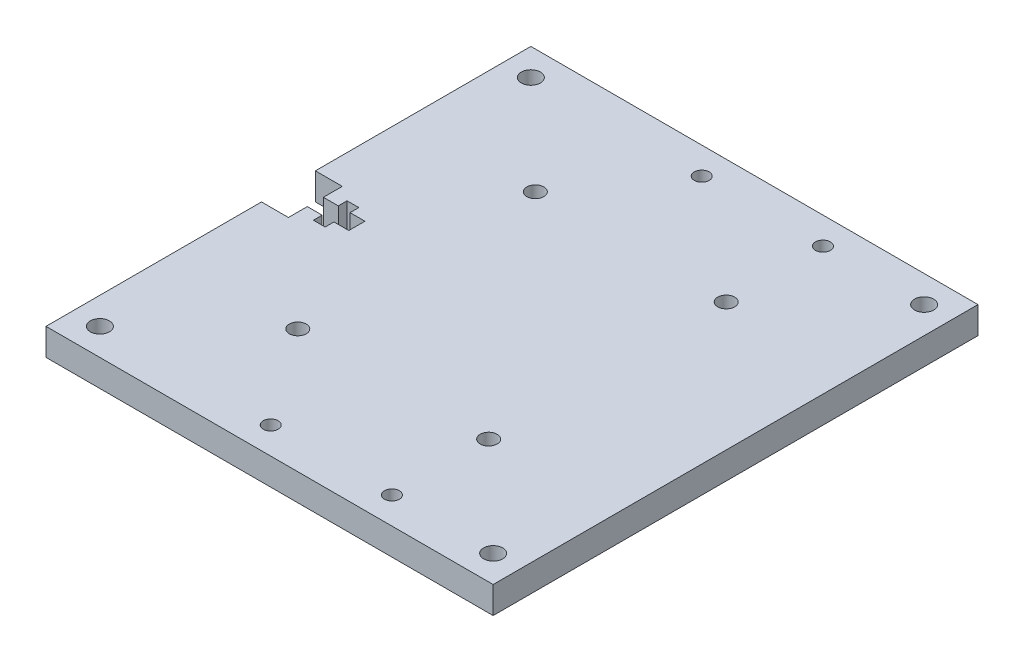
SolidWorks part; units mm, degrees
material "Beech"
ref_plane "Front Plane" through (0, 0, 0) normal (0, 0, 1) x (1, 0, 0)
ref_plane "Top Plane" through (0, 0, 0) normal (0, 1, 0) x (1, 0, 0)
ref_plane "Right Plane" through (0, 0, 0) normal (1, 0, 0) x (0, 0, -1)
sketch "Sketch1" plane through (0, 0, 0) normal (0, 1, 0) x (1, 0, 0)
  line L1 (-52.705, -57.15) -> (52.705, -57.15)
  line L2 (-52.705, -57.15) -> (-52.705, 57.15)
  line L3 (-52.705, 57.15) -> (52.705, 57.15)
  line L4 (52.705, -57.15) -> (52.705, 57.15)
  line L5 (-52.705, -57.15) -> (52.705, 57.15) construction
  line L6 (-52.705, 57.15) -> (52.705, -57.15) construction
  point P0 (0, 0)
  dimension "D1" = 105.41
  dimension "D2" = 114.3
extrude "Boss-Extrude1" add sketch "Sketch1" along normal mid plane 6.35
hole_wizard "Ø4.0 (4) Diameter Hole1" positions "Sketch3" profile "Sketch2" hole size "Ø4.0" standard "ANSI Metric" end condition up to next
sketch "Sketch3" plane through (0, 3.175, 0) normal (0, 1, 0) x (1, 0, 0)
  line L0 (52.705, 0) -> (-52.705, 0) construction
  line L1 (52.705, -57.15) -> (52.705, 57.15) construction
  line L2 (-52.705, 57.15) -> (-52.705, -57.15) construction
  line L3 (-52.705, 0) -> (0, 57.15) construction
  line L4 (52.705, 57.15) -> (-52.705, 57.15) construction
  line L5 (0, 57.15) -> (0, -57.15) construction
  line L6 (-52.705, -57.15) -> (52.705, -57.15) construction
  point P17 (22.5, 28)
  dimension "D1" = 28
  dimension "D2" = 22.5
sketch "Sketch2" plane through (22.5, 3.175, -28) normal (1, 0, 0) x (0, 0, 1)
  line L0 (0, 0) -> (0, 6.35)
  line L1 (0, 6.35) -> (2, 6.35)
  line L2 (2, 6.35) -> (2, 0)
  line L5 (2, 0) -> (0, 0)
  line L11 (0, -6.35) -> (0, 107.95) construction
  dimension "Thru Hole Dia." = 4
  dimension "Thru Hole Depth" = 6.35
pattern_linear "LPattern1" count 2 spacing 56 along (0, 0, 1) count 2 spacing 45 along (-1, 0, 0) of "Ø4.0 (4) Diameter Hole1"
hole_wizard "#8 Clearance Hole1" positions "Sketch5" profile "Sketch4" hole size "#8" standard "ANSI Inch" end condition up to next
sketch "Sketch5" plane through (0, 3.175, 0) normal (0, 1, 0) x (1, 0, 0)
  line L0 (-46.355, 57.15) -> (-46.355, -57.15) construction
  line L1 (52.705, 57.15) -> (-52.705, 57.15) construction
  line L2 (-52.705, -57.15) -> (52.705, -57.15) construction
  line L5 (52.705, 50.8) -> (-52.705, 50.8) construction
  line L6 (52.705, -57.15) -> (52.705, 57.15) construction
  line L7 (-52.705, 57.15) -> (-52.705, -57.15) construction
  point P19 (-46.355, 50.8)
  dimension "D1" = 6.35
  dimension "D2" = 6.35
sketch "Sketch4" plane through (-46.355, 3.175, -50.8) normal (1, 0, 0) x (0, 0, 1)
  line L0 (0, 0) -> (0, 6.351)
  line L1 (0, 6.351) -> (2.2479, 6.351)
  line L2 (2.2479, 6.351) -> (2.2479, 0)
  line L5 (2.2479, 0) -> (0, 0)
  line L11 (0, -6.35) -> (0, 107.95) construction
  dimension "Thru Hole Dia." = 4.4958
  dimension "Thru Hole Depth" = 6.351
mirror "Mirror1" about plane through (0, 0, 0) normal (0, 0, 1) of "#8 Clearance Hole1"
mirror "Mirror2" about plane through (0, 0, 0) normal (1, 0, 0) of "Mirror1", "#8 Clearance Hole1"
hole_wizard "#6 Clearance Hole1" positions "Sketch7" profile "Sketch6" hole size "#6" standard "ANSI Inch"
sketch "Sketch7" plane through (0, 3.175, 0) normal (0, 1, 0) x (1, 0, 0)
  line L0 (22.5, 28) -> (22.5, 57.15) construction
  line L1 (52.705, 57.15) -> (-52.705, 57.15) construction
  point P19 (22.5, 50.8)
  point P34 (-6.075, 50.8)
  dimension "D1" = 6.35
  dimension "D2" = 28.575
sketch "Sketch6" plane through (22.5, 3.175, -50.8) normal (1, 0, 0) x (0, 0, 1)
  line L0 (0, 0) -> (0, 7.4031)
  line L1 (0, 7.4031) -> (1.7526, 6.35)
  line L2 (1.7526, 6.35) -> (1.7526, 0)
  line L5 (1.7526, 0) -> (0, 0)
  line L10 (0, 7.4031) -> (-1.7526, 6.35) construction
  line L11 (0, -6.35) -> (0, 107.95) construction
  dimension "Hole Dia." = 3.5052
  dimension "Hole Depth" = 6.35
  dimension "Drill Angle" = 118
sketch "Sketch8" plane through (0, 3.175, 0) normal (0, 1, 0) x (1, 0, 0)
  line L0 (-52.705, -6.35) -> (-52.705, 6.35)
  line L1 (-52.705, -6.35) -> (-46.355, -6.35)
  line L2 (-52.705, 6.35) -> (-46.355, 6.35)
  line L3 (-40.0764, 1.8986) -> (-36.576, 1.8986)
  line L4 (-40.0764, 3.9687) -> (-40.0764, 1.8986)
  line L5 (-42.8546, 3.9687) -> (-40.0764, 3.9687)
  line L6 (-42.8546, 1.8986) -> (-42.8546, 3.9687)
  line L7 (-40.0764, -1.8986) -> (-36.576, -1.8987)
  line L8 (-40.0764, -3.9688) -> (-40.0764, -1.8986)
  line L9 (-42.8546, -3.9688) -> (-40.0764, -3.9688)
  line L10 (-42.8546, -1.8986) -> (-42.8546, -3.9688)
  line L11 (-46.355, -1.8987) -> (-42.8546, -1.8986)
  line L12 (-36.576, 1.8986) -> (-36.576, -1.8987)
  line L13 (-46.355, 1.8986) -> (-42.8546, 1.8986)
  line L14 (-46.355, 1.8986) -> (-46.355, 6.35)
  line L15 (-46.355, -6.35) -> (-46.355, -1.8987)
  line L16 (-52.705, 0) -> (-36.576, 0) construction
  line L17 (0, 0) -> (-52.705, 0) construction
  line L18 (-52.705, 57.15) -> (-52.705, -57.15) construction
  dimension "D5" = 3.7973
  dimension "D6" = 9.779
  dimension "D7" = 2.7781
  dimension "D8" = 12.7
  dimension "D9" = 6.35
  dimension "D10" = 3.9688
  dimension "D11" = 3.9688
extrude "Cut-Extrude1" cut sketch "Sketch8" against normal up to next
ref_plane "Plane1" through (-49.53, 0, 0) normal (-1, 0, 0) x (0, 0, 1)
ref_plane "Plane2" through (43.18, 0, 0) normal (1, 0, 0) x (0, 0, -1)
mirror "Mirror3" about plane through (0, 0, 0) normal (0, 0, 1) of "#6 Clearance Hole1"
